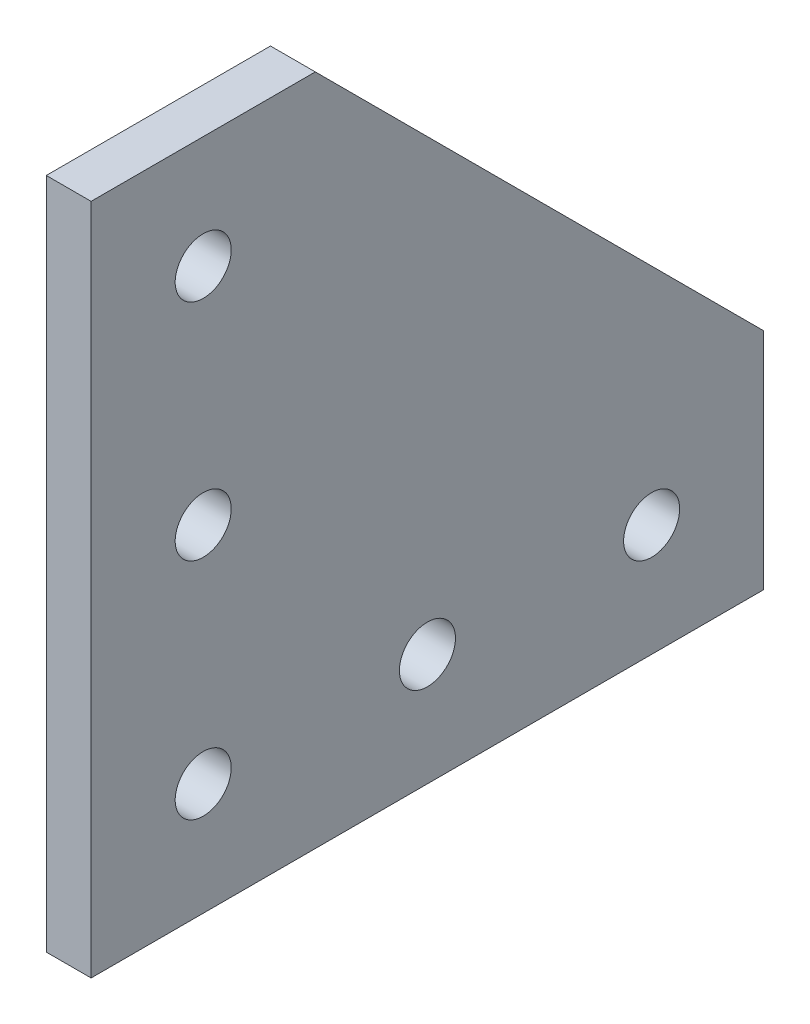
SolidWorks part; units mm, degrees
ref_plane "Front Plane" through (0, 0, 0) normal (0, 0, 1) x (1, 0, 0)
ref_plane "Top Plane" through (0, 0, 0) normal (0, 1, 0) x (1, 0, 0)
ref_plane "Right Plane" through (0, 0, 0) normal (1, 0, 0) x (0, 0, -1)
sketch "Sketch1" plane through (0, 0, 0) normal (1, 0, 0) x (0, 0, -1)
  line L0 (0, 0) -> (0, 60)
  line L1 (0, 60) -> (20, 60)
  line L2 (20, 60) -> (60, 20)
  line L3 (60, 20) -> (60, 0)
  line L4 (60, 0) -> (0, 0)
  line L5 (10, 10) -> (0, 10) construction
  line L6 (10, 10) -> (10, 0) construction
  circle A0 centre (10, 10) radius 2.5
  circle A1 centre (10, 30) radius 2.5
  circle A2 centre (10, 50) radius 2.5
  circle A3 centre (30, 10) radius 2.5
  circle A4 centre (50, 10) radius 2.5
  dimension "D3" = 5
  dimension "D1" = 20
  dimension "D2" = 60
  dimension "D4" = 10
  dimension "D5" = 3
  dimension "D6" = 20
  dimension "D8" = 20
  dimension "D7" = 3
extrude "Boss-Extrude1" add sketch "Sketch1" along normal blind 4
